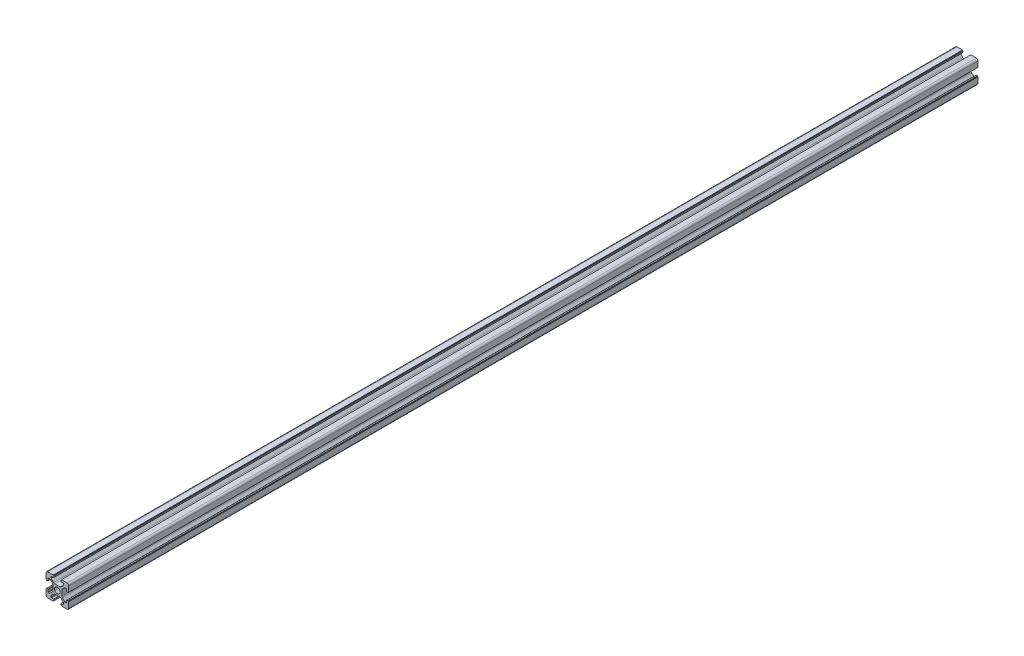
SolidWorks part; units mm, degrees
ref_plane "前视基准面" through (0, 0, 0) normal (0, 0, 1) x (1, 0, 0)
ref_plane "上视基准面" through (0, 0, 0) normal (0, 1, 0) x (1, 0, 0)
ref_plane "右视基准面" through (0, 0, 0) normal (1, 0, 0) x (0, 0, -1)
sketch "草图1" plane through (0, 0, 0) normal (0, 0, 1) x (1, 0, 0)
  line L0 (4.216, 3.2442) -> (6.4367, 5.4649)
  line L1 (6.4367, 5.4649) -> (7.7767, 5.4649)
  line L2 (8.0767, 5.1649) -> (8.0767, 3.3649)
  line L3 (8.3767, 3.0649) -> (9.3767, 3.0649)
  line L4 (9.3767, 3.0649) -> (9.3767, 3.3649)
  line L5 (9.5767, 3.5649) -> (9.8767, 3.5649)
  line L6 (9.8767, 3.5649) -> (9.8767, 8.4649)
  line L7 (8.3767, 9.9649) -> (3.4767, 9.9649)
  line L8 (3.4767, 9.9649) -> (3.4767, 9.6649)
  line L9 (3.2767, 9.4649) -> (2.9767, 9.4649)
  line L10 (2.9767, 9.4649) -> (2.9767, 8.4649)
  line L11 (3.2767, 8.1649) -> (5.0767, 8.1649)
  line L12 (5.3767, 7.8649) -> (5.3767, 6.5249)
  line L13 (5.3767, 6.5249) -> (3.156, 4.3042)
  line L14 (2.0953, 3.8649) -> (-2.342, 3.8649)
  line L15 (-3.4027, 4.3042) -> (-5.6233, 6.5249)
  line L16 (-5.6233, 6.5249) -> (-5.6233, 7.8649)
  line L17 (-5.3233, 8.1649) -> (-3.5233, 8.1649)
  line L18 (-3.2233, 8.4649) -> (-3.2233, 9.4649)
  line L19 (-3.2233, 9.4649) -> (-3.5233, 9.4649)
  line L20 (-3.7233, 9.6649) -> (-3.7233, 9.9649)
  line L21 (-3.7233, 9.9649) -> (-8.6233, 9.9649)
  line L22 (-10.1233, 8.4649) -> (-10.1233, 3.5649)
  line L23 (-10.1233, 3.5649) -> (-9.8233, 3.5649)
  line L24 (-9.6233, 3.3649) -> (-9.6233, 3.0649)
  line L25 (-9.6233, 3.0649) -> (-8.6233, 3.0649)
  line L26 (-8.3233, 3.3649) -> (-8.3233, 5.1649)
  line L27 (-8.0233, 5.4649) -> (-6.6833, 5.4649)
  line L28 (-6.6833, 5.4649) -> (-4.4627, 3.2442)
  line L29 (-4.0233, 2.1836) -> (-4.0233, -2.2538)
  line L30 (-4.4627, -3.3144) -> (-6.6833, -5.5351)
  line L31 (-6.6833, -5.5351) -> (-8.0233, -5.5351)
  line L32 (-8.3233, -5.2351) -> (-8.3233, -3.4351)
  line L33 (-8.6233, -3.1351) -> (-9.6233, -3.1351)
  line L34 (-9.6233, -3.1351) -> (-9.6233, -3.4351)
  line L35 (-9.8233, -3.6351) -> (-10.1233, -3.6351)
  line L36 (-10.1233, -3.6351) -> (-10.1233, -8.5351)
  line L37 (-8.6233, -10.0351) -> (-3.7233, -10.0351)
  line L38 (-3.7233, -10.0351) -> (-3.7233, -9.7351)
  line L39 (-3.5233, -9.5351) -> (-3.2233, -9.5351)
  line L40 (-3.2233, -9.5351) -> (-3.2233, -8.5351)
  line L41 (-3.5233, -8.2351) -> (-5.3233, -8.2351)
  line L42 (-5.6233, -7.9351) -> (-5.6233, -6.5951)
  line L43 (-5.6233, -6.5951) -> (-3.4027, -4.3744)
  line L44 (-2.342, -3.9351) -> (2.0953, -3.9351)
  line L45 (3.156, -4.3744) -> (5.3767, -6.5951)
  line L46 (5.3767, -6.5951) -> (5.3767, -7.9351)
  line L47 (5.0767, -8.2351) -> (3.2767, -8.2351)
  line L48 (2.9767, -8.5351) -> (2.9767, -9.5351)
  line L49 (2.9767, -9.5351) -> (3.2767, -9.5351)
  line L50 (3.4767, -9.7351) -> (3.4767, -10.0351)
  line L51 (3.4767, -10.0351) -> (8.3767, -10.0351)
  line L52 (9.8767, -8.5351) -> (9.8767, -3.6351)
  line L53 (9.8767, -3.6351) -> (9.5767, -3.6351)
  line L54 (9.3767, -3.4351) -> (9.3767, -3.1351)
  line L55 (9.3767, -3.1351) -> (8.3767, -3.1351)
  line L56 (8.0767, -3.4351) -> (8.0767, -5.2351)
  line L57 (7.7767, -5.5351) -> (6.4367, -5.5351)
  line L58 (6.4367, -5.5351) -> (4.216, -3.3144)
  line L59 (3.7767, -2.2538) -> (3.7767, 2.1836)
  circle A0 centre (-0.1233, -0.0351) radius 2.5
  arc A1 (8.0767, 5.1649) -> (7.7767, 5.4649) centre (7.7767, 5.1649) ccw
  arc A2 (8.0767, 3.3649) -> (8.3767, 3.0649) centre (8.3767, 3.3649) ccw
  arc A3 (9.5767, 3.5649) -> (9.3767, 3.3649) centre (9.5767, 3.3649) ccw
  arc A4 (9.8767, 8.4649) -> (8.3767, 9.9649) centre (8.3767, 8.4649) ccw
  arc A5 (3.2767, 9.4649) -> (3.4767, 9.6649) centre (3.2767, 9.6649) ccw
  arc A6 (2.9767, 8.4649) -> (3.2767, 8.1649) centre (3.2767, 8.4649) ccw
  arc A7 (5.3767, 7.8649) -> (5.0767, 8.1649) centre (5.0767, 7.8649) ccw
  arc A8 (2.0953, 3.8649) -> (3.156, 4.3042) centre (2.0953, 5.3649) ccw
  arc A9 (-3.4027, 4.3042) -> (-2.342, 3.8649) centre (-2.342, 5.3649) ccw
  arc A10 (-5.3233, 8.1649) -> (-5.6233, 7.8649) centre (-5.3233, 7.8649) ccw
  arc A11 (-3.5233, 8.1649) -> (-3.2233, 8.4649) centre (-3.5233, 8.4649) ccw
  arc A12 (-3.7233, 9.6649) -> (-3.5233, 9.4649) centre (-3.5233, 9.6649) ccw
  arc A13 (-8.6233, 9.9649) -> (-10.1233, 8.4649) centre (-8.6233, 8.4649) ccw
  arc A14 (-9.6233, 3.3649) -> (-9.8233, 3.5649) centre (-9.8233, 3.3649) ccw
  arc A15 (-8.6233, 3.0649) -> (-8.3233, 3.3649) centre (-8.6233, 3.3649) ccw
  arc A16 (-8.0233, 5.4649) -> (-8.3233, 5.1649) centre (-8.0233, 5.1649) ccw
  arc A17 (-4.0233, 2.1836) -> (-4.4627, 3.2442) centre (-5.5233, 2.1836) ccw
  arc A18 (-4.4627, -3.3144) -> (-4.0233, -2.2538) centre (-5.5233, -2.2538) ccw
  arc A19 (-8.3233, -5.2351) -> (-8.0233, -5.5351) centre (-8.0233, -5.2351) ccw
  arc A20 (-8.3233, -3.4351) -> (-8.6233, -3.1351) centre (-8.6233, -3.4351) ccw
  arc A21 (-9.8233, -3.6351) -> (-9.6233, -3.4351) centre (-9.8233, -3.4351) ccw
  arc A22 (-10.1233, -8.5351) -> (-8.6233, -10.0351) centre (-8.6233, -8.5351) ccw
  arc A23 (-3.5233, -9.5351) -> (-3.7233, -9.7351) centre (-3.5233, -9.7351) ccw
  arc A24 (-3.2233, -8.5351) -> (-3.5233, -8.2351) centre (-3.5233, -8.5351) ccw
  arc A25 (-5.6233, -7.9351) -> (-5.3233, -8.2351) centre (-5.3233, -7.9351) ccw
  arc A26 (-2.342, -3.9351) -> (-3.4027, -4.3744) centre (-2.342, -5.4351) ccw
  arc A27 (3.156, -4.3744) -> (2.0953, -3.9351) centre (2.0953, -5.4351) ccw
  arc A28 (5.0767, -8.2351) -> (5.3767, -7.9351) centre (5.0767, -7.9351) ccw
  arc A29 (3.2767, -8.2351) -> (2.9767, -8.5351) centre (3.2767, -8.5351) ccw
  arc A30 (3.4767, -9.7351) -> (3.2767, -9.5351) centre (3.2767, -9.7351) ccw
  arc A31 (8.3767, -10.0351) -> (9.8767, -8.5351) centre (8.3767, -8.5351) ccw
  arc A32 (9.3767, -3.4351) -> (9.5767, -3.6351) centre (9.5767, -3.4351) ccw
  arc A33 (8.3767, -3.1351) -> (8.0767, -3.4351) centre (8.3767, -3.4351) ccw
  arc A34 (7.7767, -5.5351) -> (8.0767, -5.2351) centre (7.7767, -5.2351) ccw
  arc A35 (3.7767, -2.2538) -> (4.216, -3.3144) centre (5.2767, -2.2538) ccw
  arc A36 (4.216, 3.2442) -> (3.7767, 2.1836) centre (5.2767, 2.1836) ccw
extrude "凸台-拉伸1" add sketch "草图1" along normal blind 800
